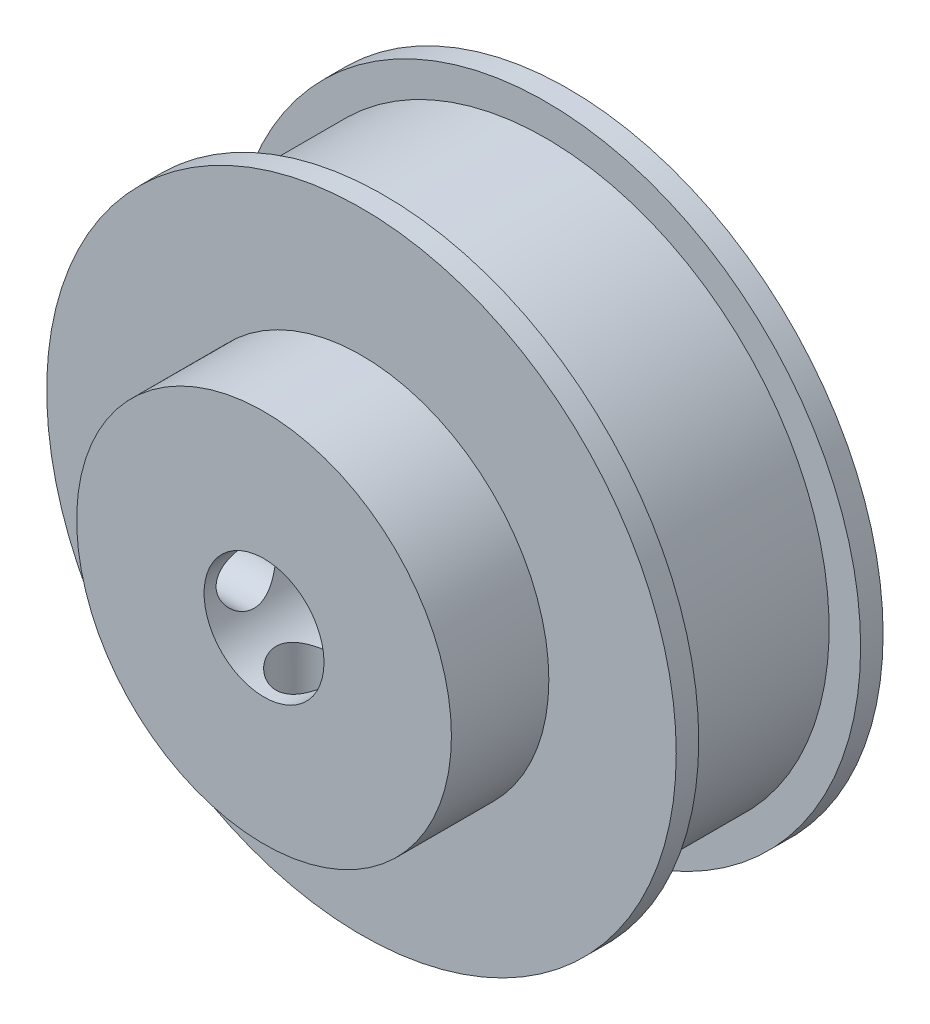
SolidWorks part; units mm, degrees
ref_plane "Alzado" through (0, 0, 0) normal (0, 0, 1) x (1, 0, 0)
ref_plane "Planta" through (0, 0, 0) normal (0, 1, 0) x (1, 0, 0)
ref_plane "Vista lateral" through (0, 0, 0) normal (1, 0, 0) x (0, 0, -1)
sketch "Croquis1" plane through (0, 0, 0) normal (0, 0, 1) x (1, 0, 0)
  circle A0 centre (0, 0) radius 21
  dimension "D1" = 42
extrude "Saliente-Extruir1" add sketch "Croquis1" along normal blind 1.5
sketch "Croquis2" plane through (0, 0, 1.5) normal (0, 0, 1) x (1, 0, 0)
  circle A0 centre (0, 0) radius 18.9
  dimension "D1" = 37.8
extrude "Saliente-Extruir2" add sketch "Croquis2" along normal blind 10.8
sketch "Croquis3" plane through (0, 0, 12.3) normal (0, 0, 1) x (1, 0, 0)
  circle A0 centre (0, 0) radius 21
  dimension "D1" = 42
extrude "Saliente-Extruir3" add sketch "Croquis3" along normal blind 1.5
sketch "Croquis8" plane through (0, 0, 13.8) normal (0, 0, 1) x (1, 0, 0)
  circle A0 centre (0, 0) radius 12.5
  dimension "D1" = 25
extrude "Saliente-Extruir5" add sketch "Croquis8" along normal blind 6.5
sketch "Croquis6" plane through (0, 0, 0) normal (0, 1, 0) x (1, 0, 0)
  line L0 (0, 0) -> (0, -17.5) construction
  circle A0 centre (0, -17.5) radius 2
  dimension "D2" = 4
  dimension "D1" = 17.5
extrude "Cortar-Extruir3" cut sketch "Croquis6" against normal through all
sketch "Croquis5" plane through (0, 0, 0) normal (1, 0, 0) x (0, 0, -1)
  line L0 (0, 0) -> (-17.5, 0) construction
  circle A0 centre (-17.5, 0) radius 2
  dimension "D2" = 4
  dimension "D1" = 17.5
extrude "Cortar-Extruir2" cut sketch "Croquis5" against normal through all
sketch "Croquis4" plane through (0, 0, 20.3) normal (0, 0, 1) x (1, 0, 0)
  circle A0 centre (0, 0) radius 4
  dimension "D1" = 8
extrude "Cortar-Extruir1" cut sketch "Croquis4" against normal through all
